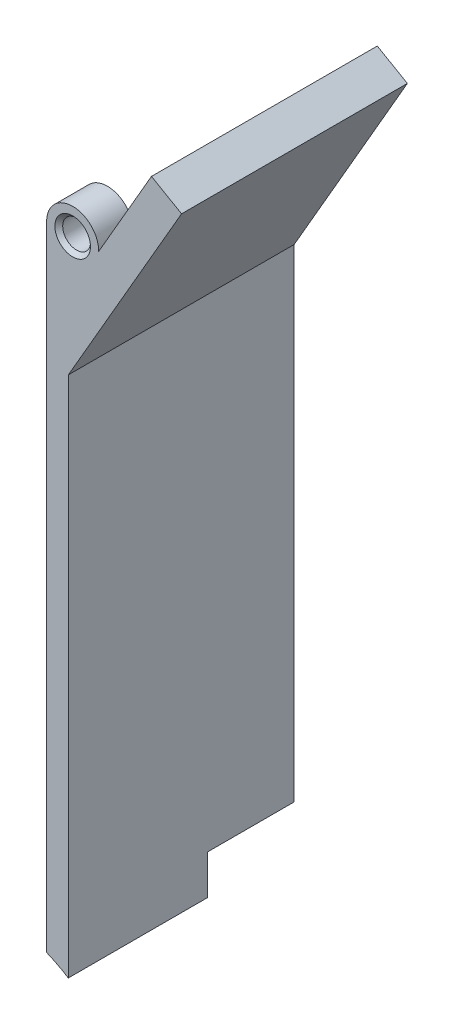
SolidWorks part; units mm, degrees
material "1060-H16"
ref_plane "前视基准面" through (0, 0, 0) normal (0, 0, 1) x (1, 0, 0)
ref_plane "上视基准面" through (0, 0, 0) normal (0, 1, 0) x (1, 0, 0)
ref_plane "右视基准面" through (0, 0, 0) normal (1, 0, 0) x (0, 0, -1)
sketch "草图1" plane through (0, 0, 0) normal (0, 0, 1) x (1, 0, 0)
  line L0 (-3.4641, -2) -> (-5.1962, -3)
  line L1 (-5.1962, -3) -> (1.3209, -14.2878)
  line L2 (1.3209, -14.2878) -> (1.3209, -44.3556)
  line L3 (2.5709, -12.4529) -> (2.5709, -43.7084)
  line L4 (2.5709, -38.4134) -> (2.5709, -44.8063) construction
  line L6 (2.5709, -12.4529) -> (-3.4641, -2)
  circle A0 centre (6.0709, -52) radius 9
  arc A1 (5.1962, 3) -> (-5.1962, -3) centre (0, 0) ccw construction
  dimension "D3" = 30.0677
  dimension "D1" = 2
  dimension "D2" = 13.0341
  dimension "D4" = 150
  dimension "D5" = 1.25
extrude "凸台-拉伸1" add sketch "草图1" against normal blind 13 from offset 2 offset against normal yes
sketch "草图2" plane through (0, 0, -15) normal (0, 0, -1) x (-1, 0, 0)
  circle A0 centre (-6.0709, -52) radius 11
extrude "切除-拉伸1" cut sketch "草图2" against normal blind 5
sketch "草图3" plane through (0, 0, -15) normal (0, 0, -1) x (-1, 0, 0)
  line L0 (-2.5709, -12.4529) -> (-2.5709, -41.5717) construction
  line L1 (-2.5709, -12.4529) -> (-2.5709, -41.5717)
  line L2 (-4.0709, -38.161) -> (-2.5709, -38.161)
  arc A0 (-1.3209, -42.0784) -> (-8.8209, -41.3493) centre (-6.0709, -52) ccw construction
  arc A1 (-1.3209, -42.0784) -> (-8.8209, -41.3493) centre (-6.0709, -52) ccw
  circle A2 centre (-4.0709, -39.661) radius 1.5
  line M2 (-2.5709, -12.4529) -> (-2.5709, -41.5717)
  dimension "D1" = 3
extrude "凸台-拉伸2" add sketch "草图3" against normal blind 2 contours A2 | A2 A1 M2 | A2 L1 L2
sketch "草图4" plane through (0, 0, -2) normal (0, 0, 1) x (1, 0, 0)
  line L0 (2.5709, -12.4529) -> (2.5709, -7.2568)
  line L1 (2.5709, -7.2568) -> (-0.4291, -7.2568)
  line L2 (2.5709, -12.4529) -> (-3.4641, -2) construction
  line L3 (-0.4291, -7.2568) -> (2.5709, -12.4529)
  circle A0 centre (1.0709, -7.2568) radius 1.5
  line M3 (2.5709, -12.4529) -> (-3.4641, -2)
  dimension "D1" = 3
extrude "凸台-拉伸3" add sketch "草图4" against normal blind 2 contours A0 L0 M3 | L3 A0 L1 | L1 A0
hole_wizard "M2 螺纹孔4" positions "草图11" profile "草图12" tap size "M2" standard "GB"
sketch "草图11" plane through (0, 0, -2) normal (0, 0, 1) x (1, 0, 0)
  point P0 (1.0709, -7.2568)
sketch "草图12" plane through (1.0709, -7.2568, -2) normal (1, 0, 0) x (0, -1, 0)
  line L0 (0, 0) -> (0, 5.6807)
  line L1 (0, 5.6807) -> (0.8, 5.2)
  line L2 (0.8, 5.2) -> (0.8, 0.225)
  line L3 (0.8, 0.225) -> (1.025, 0)
  line L5 (1.025, 0) -> (0, 0)
  line L6 (-0.8, 0.225) -> (-1.025, 0) construction
  line L10 (0, 5.6807) -> (-0.8, 5.2) construction
  line L11 (0, -6.35) -> (0, 107.95) construction
  dimension "螺纹孔钻头直径" = 1.6
  dimension "螺纹孔钻头深度" = 5.2
  dimension "近端锥形沉头孔直径" = 2.05
  dimension "近端锥形沉头孔角度" = 90
  dimension "导头角度" = 118
cosmetic thread "孔螺蚊线5" parameters "D1"=2, "D2"=2
hole_wizard "M2 螺纹孔5" positions "草图13" profile "草图14" tap size "M2" standard "GB"
sketch "草图13" plane through (0, 0, -15) normal (0, 0, -1) x (-1, 0, 0)
  point P0 (-4.0709, -39.661)
sketch "草图14" plane through (4.0709, -39.661, -15) normal (1, 0, 0) x (0, 1, 0)
  line L0 (0, 0) -> (0, 5.6807)
  line L1 (0, 5.6807) -> (0.8, 5.2)
  line L2 (0.8, 5.2) -> (0.8, 0.225)
  line L3 (0.8, 0.225) -> (1.025, 0)
  line L5 (1.025, 0) -> (0, 0)
  line L6 (-0.8, 0.225) -> (-1.025, 0) construction
  line L10 (0, 5.6807) -> (-0.8, 5.2) construction
  line L11 (0, -6.35) -> (0, 107.95) construction
  dimension "螺纹孔钻头直径" = 1.6
  dimension "螺纹孔钻头深度" = 5.2
  dimension "近端锥形沉头孔直径" = 2.05
  dimension "近端锥形沉头孔角度" = 90
  dimension "导头角度" = 118
cosmetic thread "孔螺蚊线6" parameters "D1"=2, "D2"=2
ref_plane "基准面1" through (31.3728, 0, 0) normal (1, 0, 0) x (0, 0, -1)
mirror "镜向2" about plane through (31.3728, 0, 0) normal (1, 0, 0) of bodies 109
delete or keep bodies "实体-删除/保留 1" type delete bodies bodies 109
